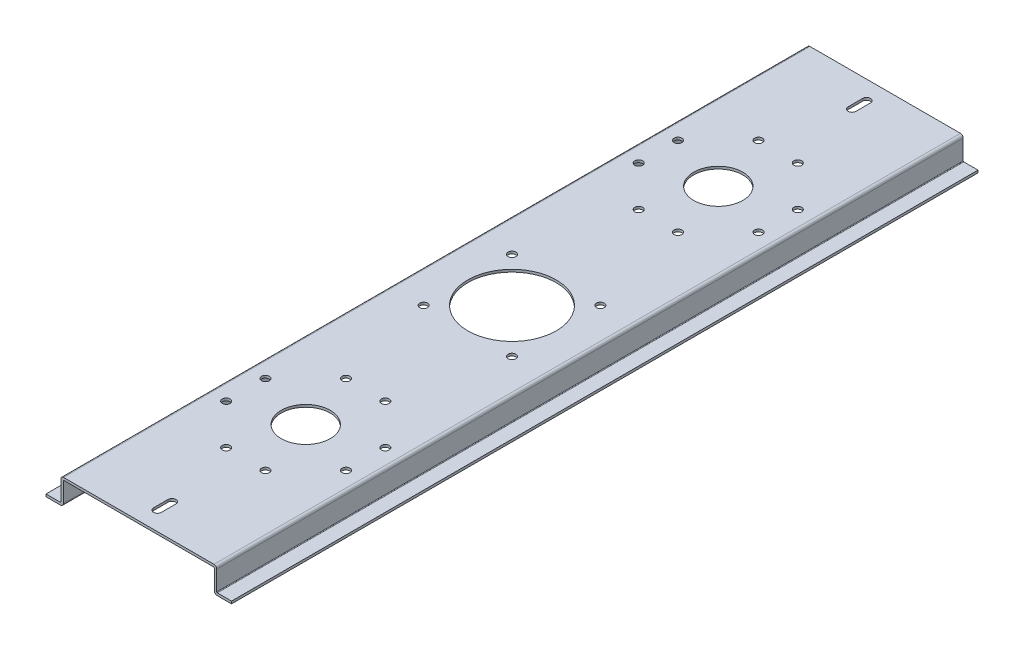
SolidWorks part; units mm, degrees
material "Plain Carbon Steel"
ref_plane "Front Plane" through (0, 0, 0) normal (0, 0, 1) x (1, 0, 0)
ref_plane "Top Plane" through (0, 0, 0) normal (0, 1, 0) x (1, 0, 0)
ref_plane "Right Plane" through (0, 0, 0) normal (1, 0, 0) x (0, 0, -1)
sketch "Sketch1" plane through (0, 0, 0) normal (0, 0, 1) x (1, 0, 0)
  line L0 (0, 0) -> (100.8063, 0)
  line L1 (100.8063, 0) -> (100.8063, -29.845)
  line L2 (100.8063, -29.845) -> (119.9515, -29.845)
  line L3 (119.9515, -29.845) -> (119.9515, -33.02)
  line L4 (119.9515, -33.02) -> (97.6313, -33.02)
  line L5 (97.6313, -33.02) -> (97.6313, -3.175)
  line L6 (-97.6313, -3.175) -> (97.6313, -3.175)
  line L7 (0, 0) -> (0, -33.02) construction
  line L13 (-100.8063, 0) -> (0, 0)
  line L14 (-119.9515, -29.845) -> (-119.9515, -33.02)
  line L15 (-100.8063, -29.845) -> (-119.9515, -29.845)
  line L16 (-119.9515, -33.02) -> (-97.6313, -33.02)
  line L17 (-97.6313, -33.02) -> (-97.6313, -3.175)
  line L18 (-100.8063, 0) -> (-100.8063, -29.845)
  point P3 (0, -3.175)
  point P11 (119.9515, -31.4325)
  dimension "D1" = 201.6125
  dimension "D2" = 3.175
  dimension "D3" = 3.175
  dimension "D4" = 3.175
  dimension "D5" = 239.903
  dimension "D6" = 33.02
  dimension "D7" = 33.02
extrude "Boss-Extrude1" add sketch "Sketch1" along normal blind 482.6 and the other way blind 482.6
sketch "Sketch2" plane through (0, 0, 0) normal (0, 1, 0) x (1, 0, 0)
  line L0 (0, 57.15) -> (57.15, 57.15) construction
  line L1 (0, -482.6) -> (0, 482.6) construction
  line L2 (100.8063, -482.6) -> (-100.8063, -482.6) construction
  line L3 (100.8063, 482.6) -> (-100.8063, 482.6) construction
  line L4 (0, -458.47) -> (0, -439.674) construction
  line L5 (-5.08, -458.47) -> (-5.08, -439.674)
  line L6 (5.08, -458.47) -> (5.08, -439.674)
  line L7 (0, -463.55) -> (6.5404, -463.55) construction
  line L8 (0, -434.594) -> (6.5404, -434.594) construction
  line L9 (0, -57.15) -> (57.15, -57.15) construction
  line L10 (0, -266.7) -> (31.75, -266.7) construction
  line L11 (0, -234.95) -> (77.47, -234.95) construction
  line L12 (77.47, -234.95) -> (77.47, -241.3) construction
  line L13 (0, 0) -> (57.15, 0) construction
  line L14 (0, 458.47) -> (0, 439.674) construction
  line L15 (-5.08, 458.47) -> (-5.08, 439.674)
  line L16 (5.08, 458.47) -> (5.08, 439.674)
  circle A0 centre (0, 0) radius 57.15
  circle A1 centre (57.15, 57.15) radius 5.08
  circle A2 centre (57.15, -57.15) radius 5.08
  circle A3 centre (-57.15, -57.15) radius 5.08
  circle A4 centre (-57.15, 57.15) radius 5.08
  arc A5 (-5.08, -458.47) -> (5.08, -458.47) centre (0, -458.47) ccw
  arc A6 (5.08, -439.674) -> (-5.08, -439.674) centre (0, -439.674) ccw
  circle A7 centre (0, -266.7) radius 31.75
  circle A8 centre (77.47, -241.3) radius 5.08
  circle A9 centre (77.47, -292.1) radius 5.08
  circle A10 centre (-25.4, -344.17) radius 5.08
  circle A11 centre (25.4, -344.17) radius 5.08
  circle A12 centre (-77.47, -241.3) radius 5.08
  circle A13 centre (-77.47, -292.1) radius 5.08
  circle A14 centre (25.4, -189.23) radius 5.08
  circle A15 centre (-25.4, -189.23) radius 5.08
  circle A16 centre (-25.4, 189.23) radius 5.08
  circle A17 centre (77.47, 241.3) radius 5.08
  circle A18 centre (25.4, 189.23) radius 5.08
  circle A19 centre (-77.47, 241.3) radius 5.08
  circle A20 centre (0, 266.7) radius 31.75
  circle A21 centre (77.47, 292.1) radius 5.08
  circle A22 centre (-77.47, 292.1) radius 5.08
  circle A23 centre (-25.4, 344.17) radius 5.08
  circle A24 centre (25.4, 344.17) radius 5.08
  arc A25 (-5.08, 458.47) -> (5.08, 458.47) centre (0, 458.47) cw
  arc A26 (5.08, 439.674) -> (-5.08, 439.674) centre (0, 439.674) cw
  point P15 (0, 0)
  point P21 (0, -449.072)
  point P55 (0, -266.7)
  point P74 (0, 449.072)
  dimension "D1" = 114.3
  dimension "D3" = 10.16
  dimension "D6" = 57.15
  dimension "D7" = 5.08
  dimension "D9" = 19.05
  dimension "D12" = 209.55
  dimension "D13" = 63.5
  dimension "D15" = 25.4
  dimension "D16" = 10.16
  dimension "D17" = 4
  dimension "D19" = 77.47
  dimension "D2" = 57.15
  dimension "D5" = 57.15
  dimension "D8" = 28.956
  dimension "D10" = 6.5404
  dimension "D11" = 6.5404
  dimension "D14" = 77.47
  dimension "D18" = 77.47
  dimension "D4" = 4
extrude "Cut-Extrude1" cut sketch "Sketch2" against normal blind 965.2
fillet "Fillet1" radius 0.7937 4 edges at (97.6313, -3.175, 0) (-97.6313, -3.175, 0) (100.8063, -29.845, 0) (-100.8063, -29.845, 0)
fillet "Fillet2" radius 3.5719 4 edges at (-100.8063, 0, 0) (100.8063, 0, 0) (-97.6313, -33.02, 0) (97.6313, -33.02, 0)
